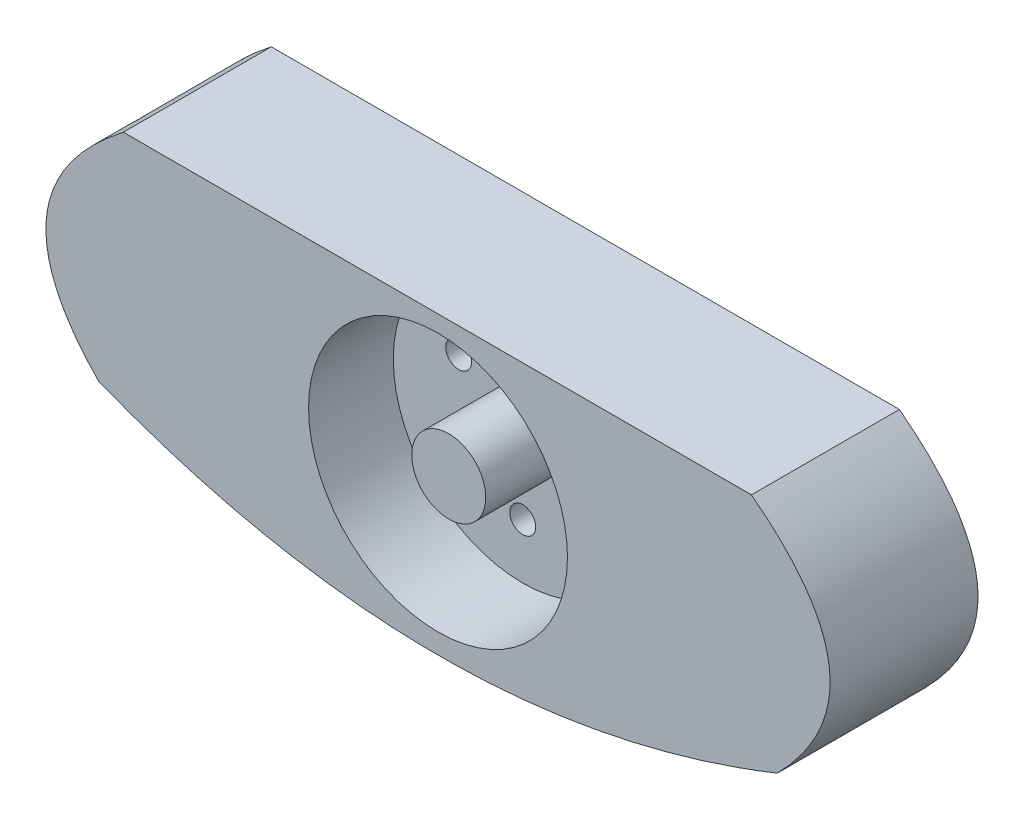
SolidWorks part; units mm, degrees
ref_plane "Front Plane" through (0, 0, 0) normal (0, 0, 1) x (1, 0, 0)
ref_plane "Top Plane" through (0, 0, 0) normal (0, 1, 0) x (1, 0, 0)
ref_plane "Right Plane" through (0, 0, 0) normal (1, 0, 0) x (0, 0, -1)
sketch "Sketch2" plane through (0, 0, 0) normal (0, 0, 1) x (1, 0, 0)
  line L1 (42.3768, 8.6832) -> (-42.5401, 8.6832)
  line L2 (42.3768, 8.6832) -> (-42.5401, 8.6832)
  parabola Q3 (45.8737, -22.1555) -> (42.3768, 8.6832) focus (46.195, -7.6248) apex (52.9944, -7.3425)
  parabola Q4 (-42.5401, 8.6832) -> (-45.8737, -22.1555) focus (-46.1445, -7.62) apex (-52.997, -7.3593)
  parabola Q5 (-45.8737, -22.1555) -> (45.8737, -22.1555) focus (0.744, 26.3908) apex (1.3864, -31.2701)
  parabola Q6 (45.8737, -22.1555) -> (42.3768, 8.6832) focus (46.195, -7.6248) apex (52.9944, -7.3425)
  parabola Q7 (-42.5401, 8.6832) -> (-45.8737, -22.1555) focus (-46.1445, -7.62) apex (-52.997, -7.3593)
  parabola Q8 (-45.8737, -22.1555) -> (45.8737, -22.1555) focus (0.744, 26.3908) apex (1.3864, -31.2701)
  dimension "D1" = 0
extrude "Boss-Extrude1" add sketch "Sketch2" along normal blind 20
sketch "Sketch4" plane through (0, 0, 20) normal (0, 0, 1) x (1, 0, 0)
  line L1 (0, -17) -> (0, -2) construction
  circle A1 centre (0, -11.063) radius 17.5
  point P5 (0, -11.063)
  dimension "D1" = 35
extrude "Cut-Extrude1" cut sketch "Sketch4" against normal blind 11.4533
sketch "Sketch5" plane through (0, 0, 8.5467) normal (0, 0, 1) x (1, 0, 0)
  line L0 (0, -17) -> (0, -2) construction
  circle A1 centre (0, -11.063) radius 5
  circle A2 centre (0, -11.063) radius 17.5 construction
  dimension "D1" = 10
extrude "Boss-Extrude2" add sketch "Sketch5" along normal blind 10
sketch "Sketch6" plane through (0, 0, 8.5467) normal (0, 0, 1) x (1, 0, 0)
  line L0 (0, -17) -> (0, -2) construction
  line L1 (0, -21.1295) -> (8.6603, -6.1295)
  line L2 (8.6603, -6.1295) -> (-8.6603, -6.1295)
  line L3 (-8.6603, -6.1295) -> (0, -21.1295)
  circle A0 centre (0, -11.1295) radius 10
  point P6 (0, 0)
  dimension "D1" = 20
hole_wizard "CBORE for M5 Hex Head Machine Screw2" positions "Sketch9" profile "Sketch10" counterbore size "M5" standard "ANSI Metric"
sketch "Sketch9" plane through (0, 0, 0) normal (0, 0, -1) x (-1, 0, 0)
  point P0 (-8.6603, -6.1295)
  point P3 (0, -21.1295)
  point P6 (8.6603, -6.1295)
sketch "Sketch10" plane through (8.6603, -6.1295, 0) normal (1, 0, 0) x (0, 1, 0)
  line L0 (0, 0) -> (0, 12.75)
  line L1 (0, 12.75) -> (1.75, 11)
  line L2 (1.75, 11) -> (1.75, 4)
  line L3 (1.75, 4) -> (3.5, 4)
  line L4 (3.5, 4) -> (3.5, 0)
  line L5 (3.5, 0) -> (0, 0)
  line L10 (0, 12.75) -> (-1.75, 11) construction
  line L11 (0, -6.35) -> (0, 107.95) construction
  dimension "Hole Dia." = 3.5
  dimension "Hole Depth" = 11
  dimension "C'Bore Dia." = 7
  dimension "C'Bore Depth" = 4
  dimension "Drill Angle" = 90
